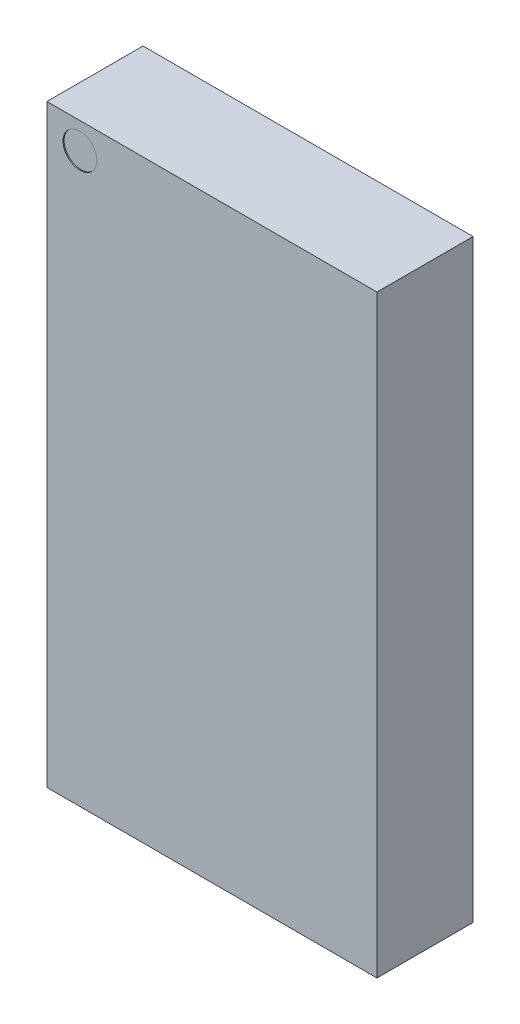
SolidWorks part; units mm, degrees
ref_plane "Front Plane" through (0, 0, 0) normal (0, 0, 1) x (1, 0, 0)
ref_plane "Top Plane" through (0, 0, 0) normal (0, 1, 0) x (1, 0, 0)
ref_plane "Right Plane" through (0, 0, 0) normal (1, 0, 0) x (0, 0, -1)
sketch "Sketch1" plane through (0, 0, 0) normal (0, 0, 1) x (1, 0, 0)
  line L1 (-3.125, -5.625) -> (3.125, -5.625)
  line L2 (-3.125, -5.625) -> (-3.125, 5.625)
  line L3 (-3.125, 5.625) -> (3.125, 5.625)
  line L4 (3.125, -5.625) -> (3.125, 5.625)
  line L5 (-3.125, -5.625) -> (3.125, 5.625) construction
  line L6 (-3.125, 5.625) -> (3.125, -5.625) construction
  point P0 (0, 0)
  dimension "D1" = 6.25
  dimension "D2" = 11.25
extrude "Boss-Extrude1" add sketch "Sketch1" along normal blind 1.82 from offset 0.4 contours L3 L4 L1 L2
sketch "Sketch3" plane through (0, 0, 0) normal (0, 1, 0) x (1, 0, 0)
  line L0 (-0.0001, -0.42) -> (0, 0)
  arc A0 (-0.0001, -0.42) -> (0, 0) centre (0, -0.21) ccw
  dimension "D1" = 0.21
revolve "Revolve1" add sketch "Sketch3" angle 360 about L0
pattern_linear "LPattern1" count 7 spacing 0.8 along (0, 1, 0) count 4 spacing 0.8 along (1, 0, 0) of "Revolve1"
pattern_linear "LPattern2" count 7 spacing 0.8 along (0, 1, 0) count 4 spacing 0.8 along (-1, 0, 0) skipping (1, 0), (2, 0), (3, 0), (4, 0), (5, 0), (6, 0) of "Revolve1"
mirror "Mirror1" about plane through (0, 0, 0) normal (0, 1, 0) of "Revolve1", "LPattern1", "LPattern2"
sketch "Sketch4" plane through (0, 0, 0.4) normal (0, 0, -1) x (-1, 0, 0)
  line L0 (2.7655, 5.5486) -> (3.0617, 5.5486)
  line L1 (3.0617, 5.5486) -> (3.0617, 5.2523)
  line L2 (3.0617, 5.2523) -> (2.7655, 5.5486)
extrude "Boss-Extrude2" add sketch "Sketch4" along normal blind 0.02
sketch "Sketch5" plane through (0, 0, 2.22) normal (0, 0, 1) x (1, 0, 0)
  circle A0 centre (-2.4998, 5.1298) radius 0.3202
extrude "Cut-Extrude1" cut sketch "Sketch5" against normal blind 0.02
